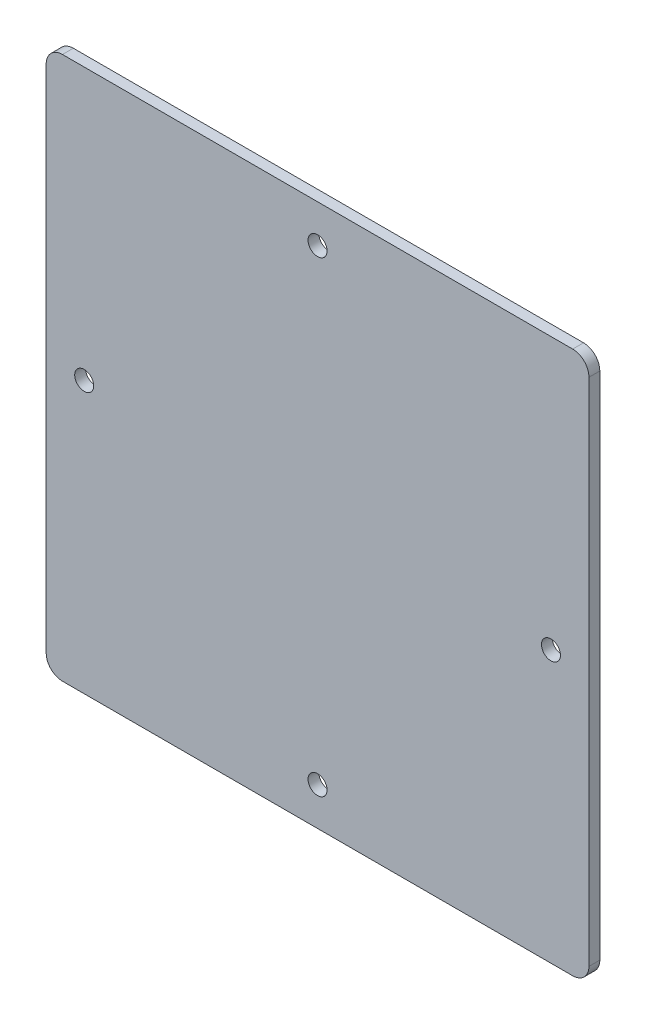
SolidWorks part; units mm, degrees
ref_plane "Plano frontal" through (0, 0, 0) normal (0, 0, 1) x (1, 0, 0)
ref_plane "Plano superior" through (0, 0, 0) normal (0, 1, 0) x (1, 0, 0)
ref_plane "Plano direito" through (0, 0, 0) normal (1, 0, 0) x (0, 0, -1)
sketch "Esboço1" plane through (0, 0, 0) normal (0, 0, 1) x (1, 0, 0)
  line L0 (0, 21.771) -> (0, 0) construction
  line L1 (-47, 50) -> (47, 50)
  line L2 (-50, 47) -> (-50, -47)
  line L3 (-47, -50) -> (47, -50)
  line L4 (50, 47) -> (50, -47)
  line L5 (-50, 50) -> (50, -50) construction
  line L6 (-50, -50) -> (50, 50) construction
  line L7 (0, 0) -> (21.5237, 0) construction
  arc A0 (-50, -47) -> (-47, -50) centre (-47, -47) ccw
  arc A1 (47, -50) -> (50, -47) centre (47, -47) ccw
  arc A2 (47, 50) -> (50, 47) centre (47, 47) cw
  arc A3 (-47, 50) -> (-50, 47) centre (-47, 47) ccw
  circle A4 centre (-43, 0) radius 1.75
  circle A5 centre (0, 43) radius 1.75
  circle A6 centre (43, 0) radius 1.75
  circle A7 centre (0, -43) radius 1.75
  point P0 (0, 0)
  point P29 (0, 0)
  dimension "D3" = 3
  dimension "D4" = 3.5
  dimension "D1" = 100
  dimension "D2" = 100
  dimension "D5" = 86
  dimension "D6" = 86
extrude "Ressalto-extrusão1" add sketch "Esboço1" along normal blind 2
